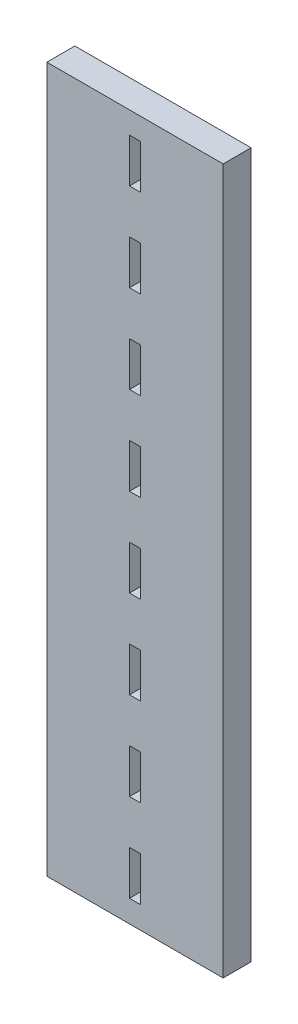
SolidWorks part; units mm, degrees
ref_plane "Front Plane" through (0, 0, 0) normal (0, 0, 1) x (1, 0, 0)
ref_plane "Top Plane" through (0, 0, 0) normal (0, 1, 0) x (1, 0, 0)
ref_plane "Right Plane" through (0, 0, 0) normal (1, 0, 0) x (0, 0, -1)
sketch "Sketch1" plane through (0, 0, 0) normal (0, 0, 1) x (1, 0, 0)
  line L0 (4.6875, 33.76) -> (4.6875, 31.26)
  line L1 (0, 40) -> (10, 40)
  line L2 (0, 40) -> (0, 0)
  line L3 (0, 0) -> (10, 0)
  line L4 (10, 40) -> (10, 0)
  line L5 (5.3125, 31.26) -> (4.6875, 31.26)
  line L6 (5.3125, 33.76) -> (5.3125, 31.26)
  line L7 (5.3125, 33.76) -> (4.6875, 33.76)
  line L8 (4.6875, 28.76) -> (4.6875, 26.26)
  line L9 (5.3125, 26.26) -> (4.6875, 26.26)
  line L10 (5.3125, 28.76) -> (5.3125, 26.26)
  line L11 (5.3125, 28.76) -> (4.6875, 28.76)
  line L12 (4.6875, 23.76) -> (4.6875, 21.26)
  line L13 (5.3125, 21.26) -> (4.6875, 21.26)
  line L14 (5.3125, 23.76) -> (5.3125, 21.26)
  line L15 (5.3125, 23.76) -> (4.6875, 23.76)
  line L16 (4.6875, 18.76) -> (4.6875, 16.26)
  line L17 (5.3125, 16.26) -> (4.6875, 16.26)
  line L18 (5.3125, 18.76) -> (5.3125, 16.26)
  line L19 (5.3125, 18.76) -> (4.6875, 18.76)
  line L20 (4.6875, 13.76) -> (4.6875, 11.26)
  line L21 (5.3125, 11.26) -> (4.6875, 11.26)
  line L22 (5.3125, 13.76) -> (5.3125, 11.26)
  line L23 (5.3125, 13.76) -> (4.6875, 13.76)
  line L24 (4.6875, 8.76) -> (4.6875, 6.26)
  line L25 (5.3125, 6.26) -> (4.6875, 6.26)
  line L26 (5.3125, 8.76) -> (5.3125, 6.26)
  line L27 (5.3125, 8.76) -> (4.6875, 8.76)
  line L28 (4.6875, 3.76) -> (4.6875, 1.26)
  line L29 (5.3125, 1.26) -> (4.6875, 1.26)
  line L30 (5.3125, 3.76) -> (5.3125, 1.26)
  line L31 (5.3125, 3.76) -> (4.6875, 3.76)
  line L64 (4.6875, 38.76) -> (4.6875, 36.26)
  line L65 (5.3125, 36.26) -> (4.6875, 36.26)
  line L66 (5.3125, 38.76) -> (5.3125, 36.26)
  line L67 (5.3125, 38.76) -> (4.6875, 38.76)
  dimension "D1" = 40
  dimension "D2" = 10
  dimension "D3" = 5.3125
  dimension "D4" = 8
extrude "Boss-Extrude2" add sketch "Sketch1" along normal blind 1.5875
